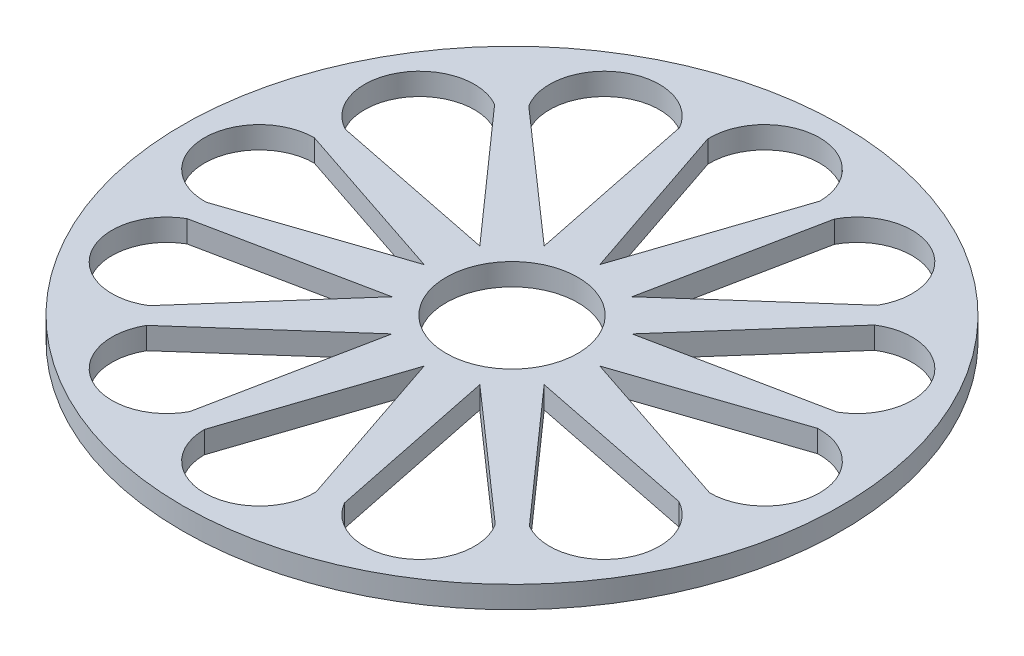
SolidWorks part; units mm, degrees
material "AISI 304"
ref_plane "前视基准面" through (0, 0, 0) normal (0, 0, 1) x (1, 0, 0)
ref_plane "上视基准面" through (0, 0, 0) normal (0, 1, 0) x (1, 0, 0)
ref_plane "右视基准面" through (0, 0, 0) normal (1, 0, 0) x (0, 0, -1)
sketch "Sketch1" plane through (0, 0, 0) normal (0, 1, 0) x (1, 0, 0)
  circle A0 centre (0, 0) radius 30
  circle A1 centre (0, 0) radius 6
  dimension "D1" = 60
  dimension "D2" = 12
extrude "Extrude1" add sketch "Sketch1" along normal blind 2
sketch "Sketch2" plane through (0, 2, 0) normal (0, 1, 0) x (1, 0, 0)
  line L0 (0, 0) -> (0, 30) construction
  line L1 (0, 23) -> (0, 13) construction
  line L4 (-5, 22.8252) -> (0, 8)
  line L5 (0, 8) -> (5.0031, 23)
  circle A0 centre (0, 0) radius 30 construction
  arc A1 (5.0031, 23) -> (-5, 22.8252) centre (0, 23) ccw
  point P7 (0, 18)
  point P12 (0, 8)
  dimension "D3" = 15
  dimension "D1" = 8
  dimension "D2" = 18
extrude "Extrude2" cut sketch "Sketch2" against normal blind 2
pattern_circular "CirPattern1" count 12 every 30 about axis through (0, 0, 0) along (0, 1, 0) of "Extrude2"
